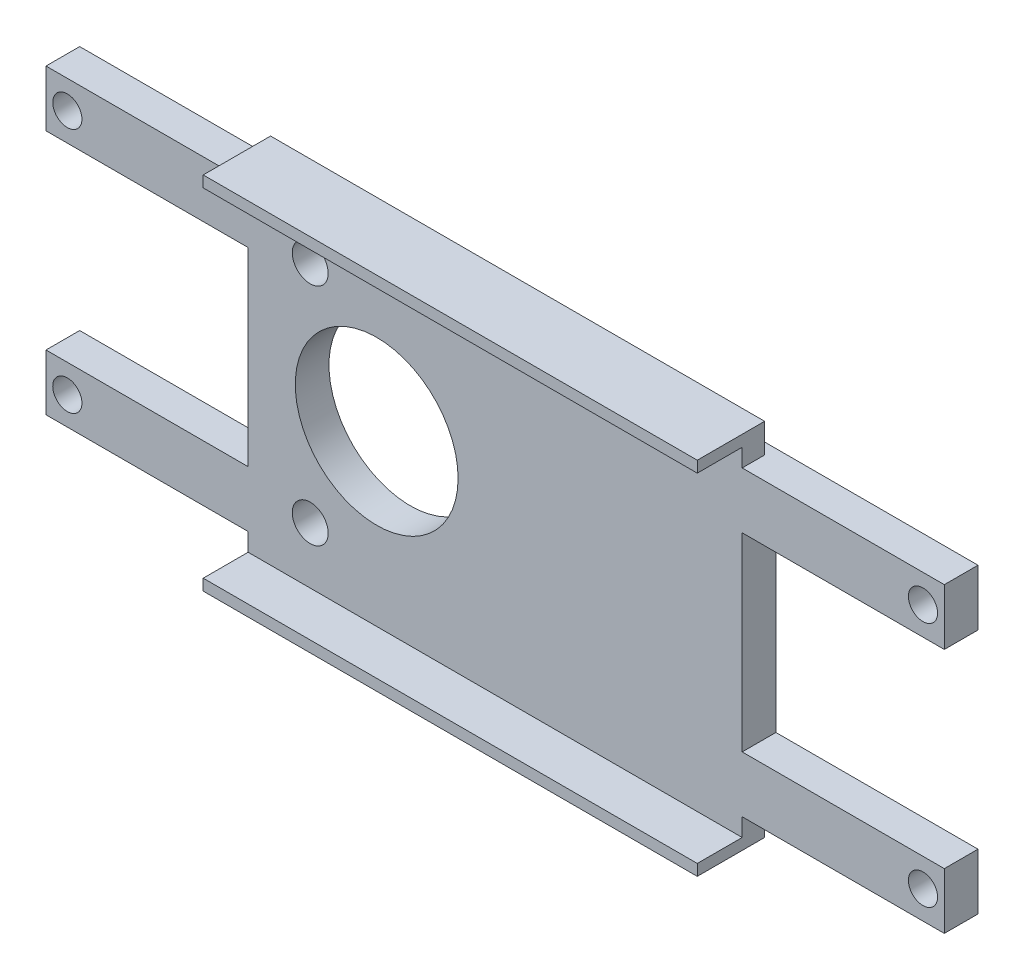
SolidWorks part; units mm, degrees
ref_plane "Plano frontal" through (0, 0, 0) normal (0, 0, 1) x (1, 0, 0)
ref_plane "Plano superior" through (0, 0, 0) normal (0, 1, 0) x (1, 0, 0)
ref_plane "Plano direito" through (0, 0, 0) normal (1, 0, 0) x (0, 0, -1)
sketch "Esboço1" plane through (0, 0, 0) normal (0, 0, 1) x (1, 0, 0)
  line L0 (-40, 0) -> (40, 0)
  line L1 (40, 0) -> (40, 5)
  line L2 (40, 21.9) -> (20, 21.9)
  line L3 (0, 49.1324) -> (0, -30.4323) construction
  line L4 (20, 21.9) -> (20, 5)
  line L5 (40, 21.9) -> (40, 26.9)
  line L6 (40, 26.9) -> (-40, 26.9)
  line L7 (20, 5) -> (40, 5)
  line L8 (-20, 5) -> (-40, 5)
  line L9 (-40, 21.9) -> (-40, 26.9)
  line L10 (-20, 21.9) -> (-20, 5)
  line L11 (-40, 21.9) -> (-20, 21.9)
  line L12 (-40, 0) -> (-40, 5)
  point P14 (0, 26.9)
  point P17 (0, 0)
  dimension "D1" = 40
  dimension "D2" = 5
  dimension "D3" = 20
  dimension "D4" = 5
  dimension "D5" = 40
  dimension "D6" = 16.9
extrude "Ressalto-extrusão1" add sketch "Esboço1" along normal blind 3
sketch "Esboço2" plane through (0, 0, 3) normal (0, 0, 1) x (1, 0, 0)
  line L0 (-40, 24.4) -> (40, 24.4) construction
  line L1 (-40, 26.9) -> (-40, 21.9) construction
  line L2 (40, 21.9) -> (40, 26.9) construction
  line L3 (-20, 13.45) -> (20, 13.45) construction
  line L4 (-20, 21.9) -> (-20, 5) construction
  line L5 (20, 5) -> (20, 21.9) construction
  circle A0 centre (-38.1, 24.4) radius 1.3
  circle A1 centre (38.1, 24.4) radius 1.3
  circle A2 centre (38.1, 2.5) radius 1.3
  circle A3 centre (-38.1, 2.5) radius 1.3
  dimension "D1" = 2.6
  dimension "D2" = 1.9
  dimension "D3" = 2.6
  dimension "D4" = 1.9
extrude "Corte-extrusão1" cut sketch "Esboço2" against normal blind 3
sketch "Esboço3" plane through (0, 0, 3) normal (0, 0, 1) x (1, 0, 0)
  line L0 (-20, 13.45) -> (20, 13.45) construction
  line L1 (-20, 21.9) -> (-20, 5) construction
  line L2 (20, 5) -> (20, 21.9) construction
  line L13 (-20, 21.9) -> (-20, 5)
  line L14 (-20, 5) -> (-22, 5)
  line L15 (-20, 5) -> (-40, 5) construction
  line L16 (-22, 5) -> (-22, 21.9)
  line L17 (-40, 21.9) -> (-20, 21.9) construction
  line L18 (-22, 21.9) -> (-20, 21.9)
  line L19 (20, 21.9) -> (20, 5)
  line L20 (20, 5) -> (22, 5)
  line L21 (40, 5) -> (20, 5) construction
  line L22 (22, 5) -> (22, 21.9)
  line L23 (20, 21.9) -> (40, 21.9) construction
  line L24 (22, 21.9) -> (20, 21.9)
extrude "Ressalto-extrusão2" add sketch "Esboço3" against normal blind 3
sketch "Esboço4" plane through (0, 0, 3) normal (0, 0, 1) x (1, 0, 0)
  line L11 (-22, 21.9) -> (-22, 5) construction
  circle A0 centre (-10.55, 13.45) radius 7.25
  point P0 (-22, 13.45)
  dimension "D2" = 14.5
  dimension "D3" = 11.45
  dimension "D1" = 0
extrude "Corte-extrusão2" cut sketch "Esboço4" against normal blind 3
sketch "Esboço6" plane through (0, 0, 3) normal (0, 0, 1) x (1, 0, 0)
  line L0 (-22, 13.45) -> (-12.0542, 13.45) construction
  line L7 (-22, 21.9) -> (-22, 5) construction
  circle A1 centre (-16.47, 23.47) radius 1.6
  circle A2 centre (-16.47, 3.43) radius 1.6
  dimension "D1" = 10.02
  dimension "D2" = 10.02
extrude "Corte-extrusão3" cut sketch "Esboço6" against normal blind 3
sketch "Esboço7" plane through (0, 0, 3) normal (0, 0, 1) x (1, 0, 0)
  line L0 (-22, 13.45) -> (33.8376, 13.45) construction
  line L1 (-22, 21.9) -> (-22, 5) construction
  line L2 (-22, 26.9) -> (-22, 29.5)
  line L3 (40, 26.9) -> (-40, 26.9) construction
  line L4 (-22, 29.5) -> (22, 29.5)
  line L5 (22, 29.5) -> (22, 26.9)
  line L6 (22, 26.9) -> (-22, 26.9)
  line L7 (22, 0) -> (-22, 0)
  line L8 (22, -2.6) -> (22, 0)
  line L9 (-22, 0) -> (-22, -2.6)
  line L10 (-22, -2.6) -> (22, -2.6)
extrude "Ressalto-extrusão4" add sketch "Esboço7" against normal blind 2
sketch "Esboço8" plane through (0, 0, 3) normal (0, 0, 1) x (1, 0, 0)
  line L0 (22, 26.9) -> (22, 29.5) construction
  line L2 (-22, 29.5) -> (22, 29.5)
  line L3 (-22, 29.5) -> (-22, 28.5)
  line L4 (-22, 28.5) -> (22, 28.5)
  line L5 (22, 29.5) -> (22, 28.5)
  line L6 (-22, 13.45) -> (-19.1658, 13.45) construction
  line L7 (-22, 21.9) -> (-22, 5) construction
  line L8 (22, -2.6) -> (22, -1.6)
  line L9 (-22, -1.6) -> (22, -1.6)
  line L10 (-22, -2.6) -> (-22, -1.6)
  line L11 (-22, -2.6) -> (22, -2.6)
  dimension "D1" = 1
extrude "Ressalto-extrusão5" add sketch "Esboço8" along normal blind 4
